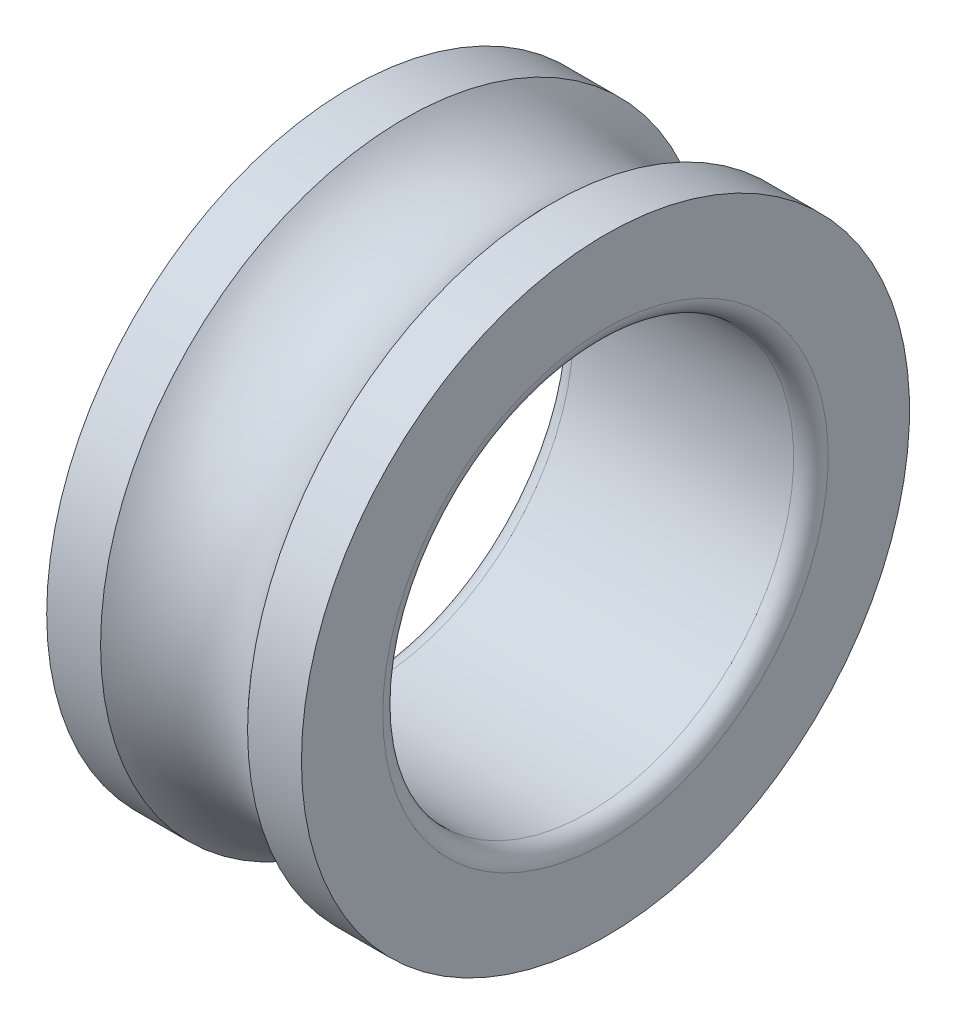
SolidWorks part; units mm, degrees
ref_plane "Front Plane" through (0, 0, 0) normal (0, 0, 1) x (1, 0, 0)
ref_plane "Top Plane" through (0, 0, 0) normal (0, 1, 0) x (1, 0, 0)
ref_plane "Right Plane" through (0, 0, 0) normal (1, 0, 0) x (0, 0, -1)
sketch "Sketch1" plane through (0, 0, 0) normal (0, 0, 1) x (1, 0, 0)
  line L0 (-22.7189, 0) -> (22.7189, 0) construction
  line L1 (0, 0) -> (0, 25) construction
  line L2 (-15.5, 37) -> (-8.9443, 37)
  line L3 (-15.5, 37) -> (-15.5, 27.1)
  line L4 (-13.4, 25) -> (13.4, 25)
  line L5 (15.5, 37) -> (15.5, 27.1)
  line L6 (-15.5, 37) -> (15.5, 25) construction
  line L7 (-15.5, 25) -> (15.5, 37) construction
  line L8 (8.9443, 37) -> (15.5, 37)
  arc A0 (8.9443, 37) -> (-8.9443, 37) centre (0, 45) cw
  arc A1 (13.4, 25) -> (15.5, 27.1) centre (13.4, 27.1) ccw
  arc A2 (-15.5, 27.1) -> (-13.4, 25) centre (-13.4, 27.1) ccw
  point P0 (0, 31)
  point P4 (0, 0)
  dimension "D5" = 12
  dimension "D6" = 2.1
  dimension "D1" = 31
  dimension "D2" = 25
  dimension "D3" = 37
  dimension "D4" = 8
revolve "Revolve1" add sketch "Sketch1" angle 360 about L0
